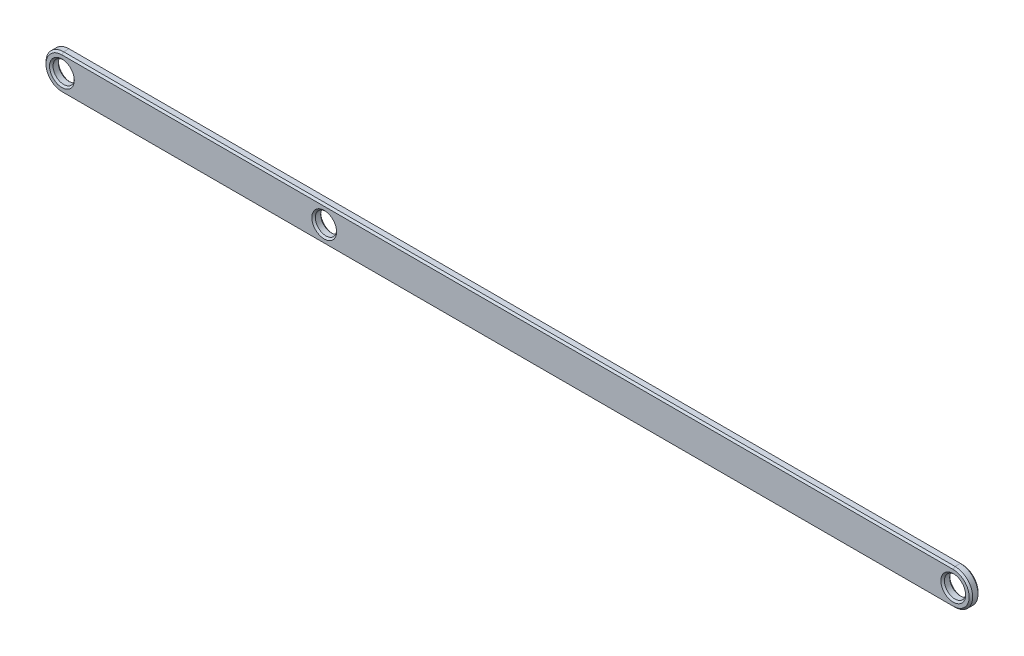
SolidWorks part; units mm, degrees
ref_plane "Front Plane" through (0, 0, 0) normal (0, 0, 1) x (1, 0, 0)
ref_plane "Top Plane" through (0, 0, 0) normal (0, 1, 0) x (1, 0, 0)
ref_plane "Right Plane" through (0, 0, 0) normal (1, 0, 0) x (0, 0, -1)
sketch "Sketch1" plane through (0, 0, 0) normal (0, 0, 1) x (1, 0, 0)
  line L0 (0, 157.4916) -> (0, -223.2358) construction
  line L1 (1260, -50) -> (-1260, -50)
  line L3 (1260, 50) -> (-1260, 50)
  line L4 (-1260, 0) -> (1260, 0) construction
  arc A0 (-1260, 50) -> (-1260, -50) centre (-1260, 0) ccw
  circle A1 centre (-1260, 0) radius 30
  arc A2 (1260, 50) -> (1260, -50) centre (1260, 0) cw
  circle A3 centre (1260, 0) radius 30
  circle A4 centre (-518.4, 0) radius 30
  point P0 (0, 0)
  dimension "D1" = 60
  dimension "D4" = 60
  dimension "D2" = 20
  dimension "D5" = 741.6
  dimension "D3" = 2520
extrude "Boss-Extrude1" add sketch "Sketch1" along normal blind 25
chamfer "Chamfer1" distance 5 angle 45 14 edges at (1230, 0, 0) (-1230, 0, 0) (0, -50, 0) (1310, 0, 0) (0, 50, 0) (-1310, 0, 0) (1230, 0, 25) (0, 50, 25) (1310, 0, 25) (0, -50, 25) (-1310, 0, 25) (-1230, 0, 25) (-488.4, 0, 0) (-488.4, 0, 25)
equation "\"length\"= 2520"
equation "\"D\"= 60"
equation "\"Mid Hole\"= 741.6"
equation "\"D5@Sketch1\"=\"Mid Hole\""
equation "\"D3@Sketch1\"=\"length\""
